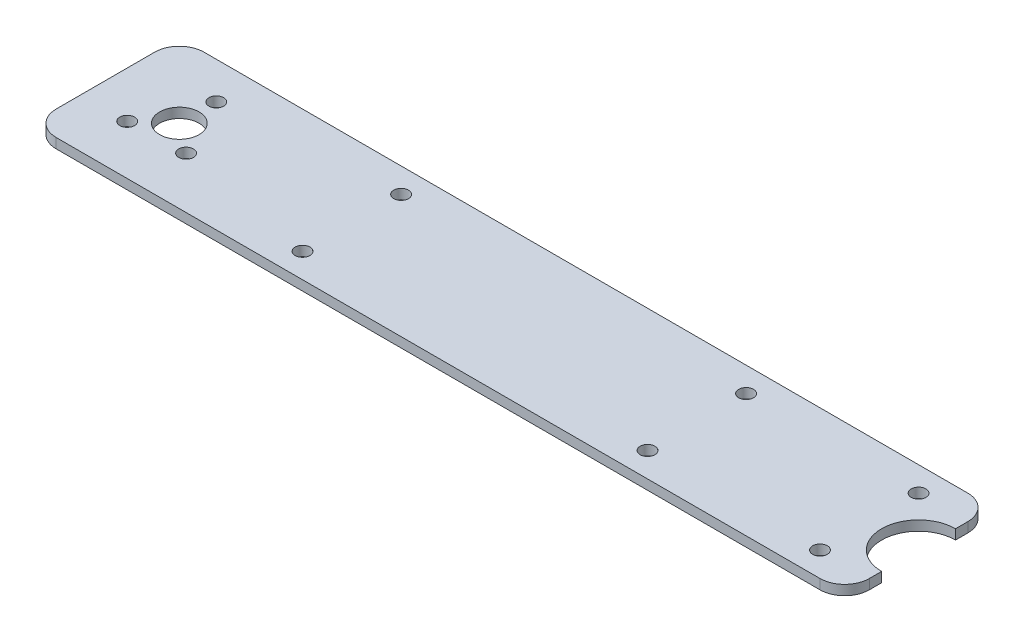
SolidWorks part; units mm, degrees
ref_plane "Front Plane" through (0, 0, 0) normal (0, 0, 1) x (1, 0, 0)
ref_plane "Top Plane" through (0, 0, 0) normal (0, 1, 0) x (1, 0, 0)
ref_plane "Right Plane" through (0, 0, 0) normal (1, 0, 0) x (0, 0, -1)
sketch "Sketch1" plane through (0, 0, 0) normal (0, 1, 0) x (1, 0, 0)
  line L1 (-82.5, 15) -> (82.5, 15)
  line L2 (-82.5, 15) -> (-82.5, -15)
  line L3 (-82.5, -15) -> (82.5, -15)
  line L4 (82.5, 15) -> (82.5, -15)
  line L5 (-82.5, 15) -> (82.5, -15) construction
  line L6 (-82.5, -15) -> (82.5, 15) construction
  point P0 (0, 0)
  dimension "D1" = 165
  dimension "D2" = 30
extrude "Boss-Extrude1" add sketch "Sketch1" along normal blind 2
fillet "Fillet1" radius 5 4 edges at (82.5, 1, 15) (82.5, 1, -15) (-82.5, 1, -15) (-82.5, 1, 15)
sketch "Sketch3" plane through (0, 2, 0) normal (0, 1, 0) x (1, 0, 0)
  line L0 (-67.5, 0) -> (-67.5, 16.9727) construction
  line L1 (-97.2806, 0) -> (-55.6726, 0) construction
  line L3 (-67.5, 0) -> (-48.4021, -14.689) construction
  line L4 (-67.5, 0) -> (-82.8755, -13.527) construction
  line L5 (-67.5, 0) -> (-67.5, -28.9997) construction
  circle A0 centre (-67.5, 0) radius 4
  circle A1 centre (-67.5, 7.5) radius 1.5
  circle A2 centre (-61.5551, -4.5725) radius 1.5
  circle A3 centre (-73.131, -4.954) radius 1.5
  point P7 (-73.131, -4.954)
  point P14 (-61.5551, -4.5725)
  point P15 (-67.5, 7.5)
  dimension "D2" = 3
  dimension "D3" = 3
  dimension "D4" = 3
  dimension "D7" = 101.094
  dimension "D8" = 13.6678
  dimension "D9" = 13.4569
  dimension "D1" = 8
  dimension "D5" = 127.565
  dimension "D6" = 131.34
  dimension "D10" = 11.5759
  dimension "D11" = 7.5
  dimension "D12" = 7.5
  dimension "D13" = 7.5
extrude "Cut-Extrude1" cut sketch "Sketch3" against normal blind 2
sketch "Sketch4" plane through (0, 2, 0) normal (0, 1, 0) x (1, 0, 0)
  line L0 (91.6385, 0) -> (59.0764, 0) construction
  line L1 (82.5, -10) -> (82.5, 10) construction
  circle A0 centre (82.5, 0) radius 7.5
  dimension "D1" = 15
extrude "Cut-Extrude2" cut sketch "Sketch4" against normal blind 10
sketch "Sketch5" plane through (0, 2, 0) normal (0, 1, 0) x (1, 0, 0)
  line L0 (-60.8984, 10) -> (49.581, 10) construction
  line L1 (-60.8984, -10) -> (51.7367, -10) construction
  line L2 (77.5, 15) -> (-77.5, 15) construction
  line L3 (-77.5, -15) -> (77.5, -15) construction
  line L4 (-82.5, 10) -> (-82.5, -10) construction
  circle A0 centre (-32.5, 10) radius 1.5
  circle A1 centre (37.5, 10) radius 1.5
  circle A2 centre (-32.5, -10) radius 1.5
  circle A3 centre (37.5, -10) radius 1.5
  dimension "D3" = 3
  dimension "D1" = 5
  dimension "D2" = 5
  dimension "D4" = 50
  dimension "D5" = 50
  dimension "D6" = 120
  dimension "D7" = 120
extrude "Cut-Extrude3" cut sketch "Sketch5" against normal blind 10
sketch "Sketch6" plane through (0, 2, 0) normal (0, 1, 0) x (1, 0, 0)
  line L0 (72.5, 21.9211) -> (72.5, -25.7122) construction
  line L1 (62.0696, 10) -> (91.6184, 10) construction
  line L2 (64.8146, -10) -> (95.3322, -10) construction
  line L3 (82.5, 7.5) -> (82.5, 10) construction
  line L4 (77.5, 15) -> (-77.5, 15) construction
  line L5 (-77.5, -15) -> (77.5, -15) construction
  circle A0 centre (72.5, 10) radius 1.5
  circle A1 centre (72.5, -10) radius 1.5
  point P12 (72.5, 10)
  point P13 (72.5, -10)
  dimension "D4" = 3
  dimension "D5" = 3
  dimension "D1" = 10
  dimension "D2" = 5
  dimension "D3" = 5
extrude "Cut-Extrude4" cut sketch "Sketch6" against normal through all
